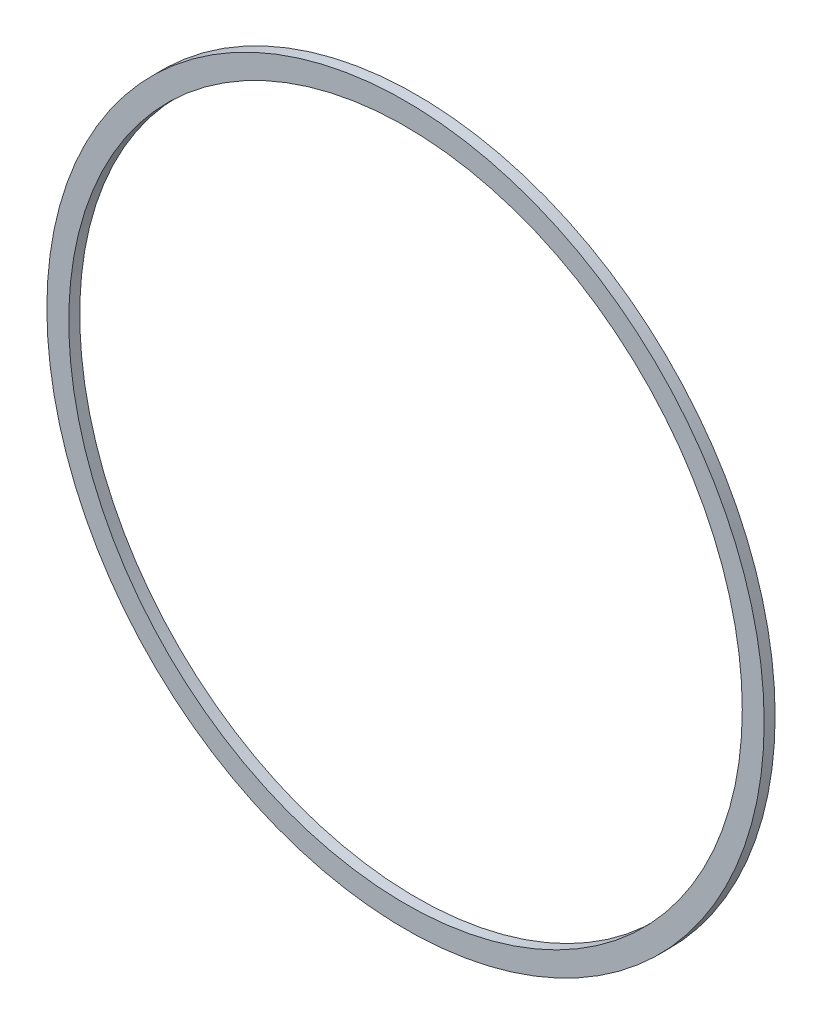
SolidWorks part; units mm, degrees
material "EPICHLOROHYDRIN"
ref_plane "Front Plane" through (0, 0, 0) normal (0, 0, 1) x (1, 0, 0)
ref_plane "Top Plane" through (0, 0, 0) normal (0, 1, 0) x (1, 0, 0)
ref_plane "Right Plane" through (0, 0, 0) normal (1, 0, 0) x (0, 0, -1)
sketch "Sketch2" plane through (0, 0, 0) normal (0, 0, 1) x (1, 0, 0)
  circle A0 centre (0, 0) radius 41.5925
  circle A1 centre (0, 0) radius 39.0525
  dimension "D1" = 83.185
  dimension "D2" = 2.54
extrude "Boss-Extrude1" add sketch "Sketch2" along normal blind 1.27
